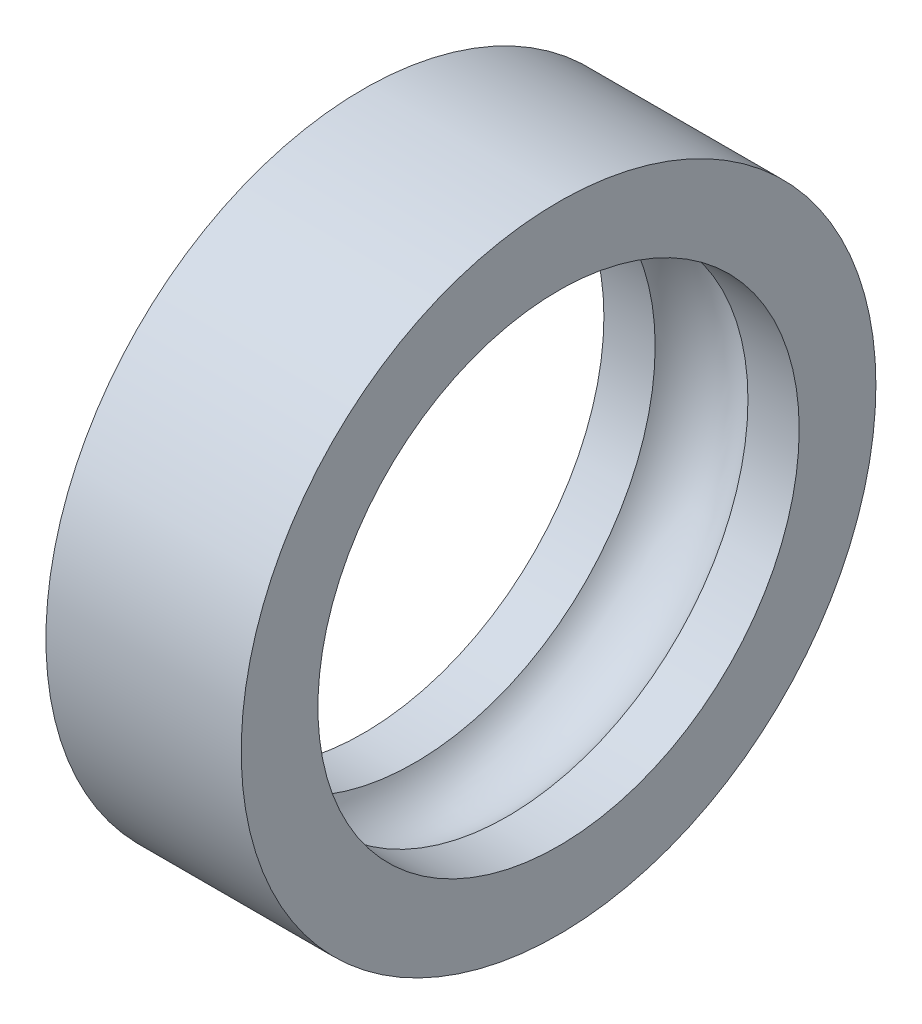
SolidWorks part; units mm, degrees
material "1060 Alloy"
ref_plane "Front Plane" through (0, 0, 0) normal (0, 0, 1) x (1, 0, 0)
ref_plane "Top Plane" through (0, 0, 0) normal (0, 1, 0) x (1, 0, 0)
ref_plane "Right Plane" through (0, 0, 0) normal (1, 0, 0) x (0, 0, -1)
sketch "Sketch1" plane through (0, 0, 0) normal (0, 0, 1) x (1, 0, 0)
  line L0 (0, 0) -> (13.3111, 0) construction
  line L1 (13.3111, 0) -> (13.3111, 1.108) construction
  line L2 (0, 0) -> (0, 4.25) construction
  line L3 (0, 4.25) -> (4, 4.25)
  line L4 (0, 4.25) -> (-4, 4.25)
  line L5 (4, 4.25) -> (4, 1.108)
  line L6 (-4, 4.25) -> (-4, 1.108)
  line L7 (-4, 1.108) -> (-1.9006, 1.108)
  line L8 (4, 1.108) -> (1.9006, 1.108)
  line L9 (4, 4.25) -> (4, -8.75) construction
  line L10 (4, -8.75) -> (-4, -8.75) construction
  arc A0 (1.9006, 1.108) -> (-1.9006, 1.108) centre (0, 0) ccw
  dimension "D1" = 4.4
  dimension "D2" = 1.108
  dimension "D3" = 4.25
  dimension "D4" = 4
  dimension "D5" = 4
  dimension "D6" = 3.142
  dimension "D7" = 13
revolve "Revolve1" add sketch "Sketch1" angle 360 about L10
scale "Scale1" [suppressed]
scale "Scale2" scale about centroid uniform scaling yes scale factor 6
scale "Scale3" bodies to scale 106 scale about centroid uniform scaling yes scale factor 3.323882
scale "Scale4" [suppressed]
scale "Scale5" [suppressed]
scale "Scale6" [suppressed]
